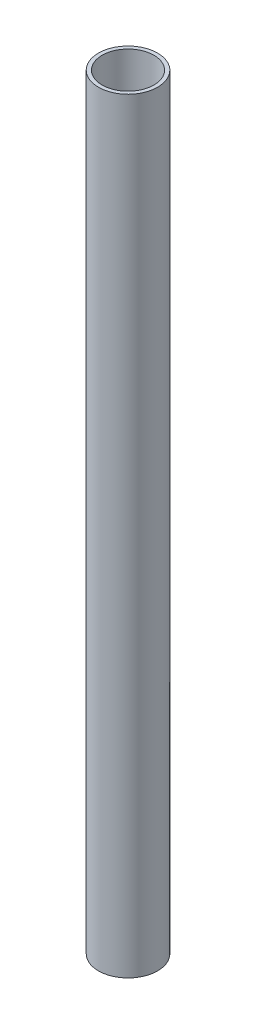
SolidWorks part; units mm, degrees
ref_plane "Front Plane" through (0, 0, 0) normal (0, 0, 1) x (1, 0, 0)
ref_plane "Top Plane" through (0, 0, 0) normal (0, 1, 0) x (1, 0, 0)
ref_plane "Right Plane" through (0, 0, 0) normal (1, 0, 0) x (0, 0, -1)
sketch "Sketch1" plane through (0, 0, 0) normal (0, 1, 0) x (1, 0, 0)
  circle A0 centre (0, 0) radius 8
  circle A1 centre (0, 0) radius 7
extrude "Boss-Extrude1" add sketch "Sketch1" along normal blind 207
